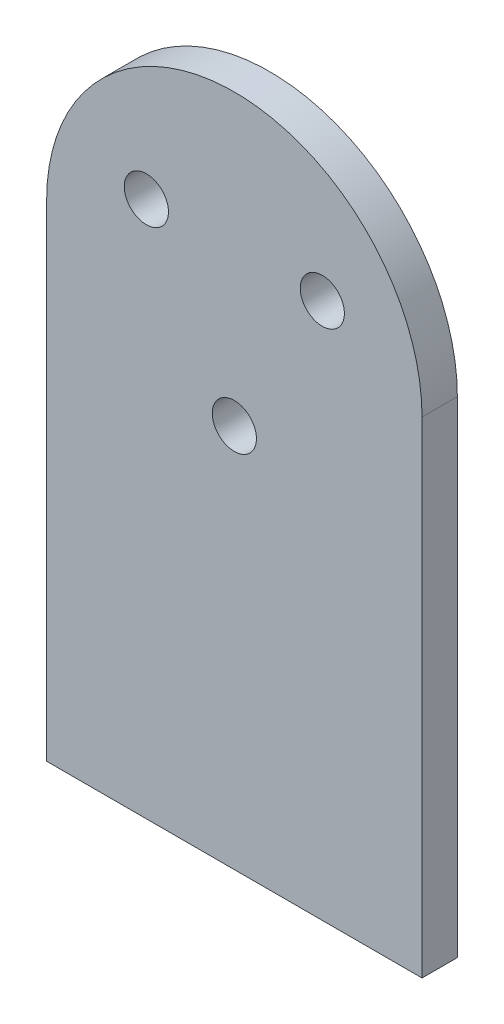
SolidWorks part; units mm, degrees
ref_plane "Front Plane" through (0, 0, 0) normal (0, 0, 1) x (1, 0, 0)
ref_plane "Top Plane" through (0, 0, 0) normal (0, 1, 0) x (1, 0, 0)
ref_plane "Right Plane" through (0, 0, 0) normal (1, 0, 0) x (0, 0, -1)
sketch "Sketch1" plane through (0, 0, 0) normal (0, 0, 1) x (1, 0, 0)
  line L0 (4.25, 0) -> (4.25, -11)
  line L1 (4.25, -11) -> (-4.25, -11)
  line L2 (-4.25, -11) -> (-4.25, 0)
  arc A0 (4.25, 0) -> (-4.25, 0) centre (0, 0) ccw
  circle A1 centre (0, -2.3) radius 0.5
  circle A2 centre (-1.9919, 1.15) radius 0.5
  circle A3 centre (1.9919, 1.15) radius 0.5
  point P14 (0, 0)
  dimension "D1" = 8.5
  dimension "D4" = 1
  dimension "D2" = 11
  dimension "D3" = 2.3
  dimension "D5" = 3
extrude "Boss-Extrude1" add sketch "Sketch1" along normal blind 0.8
